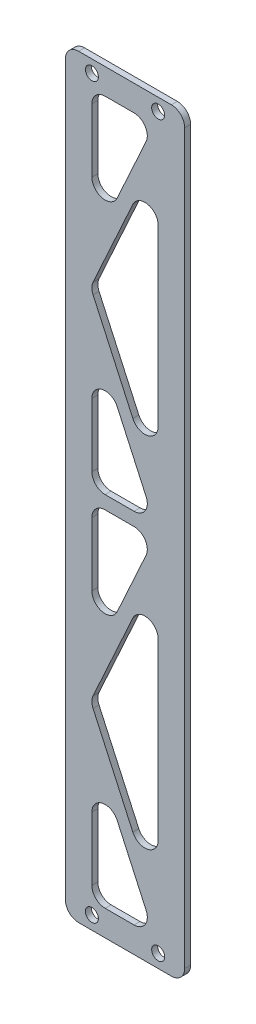
SolidWorks part; units mm, degrees
material "6061-T6 (SS)"
ref_plane "Front Plane" through (0, 0, 0) normal (0, 0, 1) x (1, 0, 0)
ref_plane "Top Plane" through (0, 0, 0) normal (0, 1, 0) x (1, 0, 0)
ref_plane "Right Plane" through (0, 0, 0) normal (1, 0, 0) x (0, 0, -1)
sketch "Sketch1" plane through (0, 0, 0) normal (0, 0, 1) x (1, 0, 0)
  line L0 (-5.08, -5.08) -> (30.48, -5.08)
  line L1 (35.56, 0) -> (35.56, 279.4)
  line L2 (30.48, 284.48) -> (-5.08, 284.48)
  line L3 (-10.16, 279.4) -> (-10.16, 0)
  line L6 (16.1606, 274.32) -> (0, 274.32)
  line L7 (0, 274.32) -> (0, 107.6181)
  line L10 (28.1496, 4.7625) -> (-49966.223, 4.7625) construction
  line L11 (20.7828, 11.9499) -> (9.7022, 36.253)
  line L12 (1052.7568, 4.7625) -> (24.0598, 4.7625) construction
  line L14 (5.08, 4.7625) -> (16.1606, 4.7625)
  line L15 (0.4578, 68.7744) -> (15.6978, 35.3485)
  line L17 (0, 34.1456) -> (0, 9.8425)
  line L18 (0, 70.8819) -> (-50000, 70.8819) construction
  line L19 (0.4578, 72.9893) -> (15.6978, 106.4153)
  line L20 (0, 107.6181) -> (0, 131.9213)
  line L21 (20.7828, 129.8138) -> (9.7022, 105.5107)
  line L22 (5.08, 137.0013) -> (16.1606, 137.0013)
  line L23 (12.7, -5.08) -> (12.7, 49994.92) construction
  line L24 (-10.16, 139.5413) -> (-50010.16, 139.5412) construction
  line L25 (30.48, -5.3975) -> (-5.08, -5.3975)
  line L26 (35.56, 279.0825) -> (35.56, -0.3175)
  line L27 (-5.08, 284.1625) -> (30.48, 284.1625)
  line L28 (-10.16, -0.3175) -> (-10.16, 279.0825)
  line L29 (0.4578, 210.3081) -> (15.6978, 243.734)
  line L30 (0.4578, 206.0932) -> (15.6978, 172.6672)
  line L31 (20.7828, 149.2687) -> (9.7022, 173.5718)
  line L32 (5.08, 142.0813) -> (16.1606, 142.0813)
  line L33 (0, 171.4644) -> (0, 147.1612)
  line L34 (0, 244.9369) -> (0, 269.24)
  line L35 (20.7828, 267.1326) -> (9.7022, 242.8295)
  line L36 (5.08, 274.32) -> (16.1606, 274.32)
  line L37 (25.4, 174.7746) -> (25.4, 241.6266)
  line L38 (25.4, 104.3079) -> (25.4, 37.4559)
  arc A24 (-5.08, 284.48) -> (-10.16, 279.4) centre (-5.08, 279.4) ccw
  arc A25 (35.56, 279.4) -> (30.48, 284.48) centre (30.48, 279.4) ccw
  arc A26 (30.48, -5.08) -> (35.56, 0) centre (30.48, 0) ccw
  arc A27 (-5.08, -5.08) -> (-10.16, 0) centre (-5.08, 0) cw
  arc A28 (0.4578, 72.9893) -> (0.4578, 68.7744) centre (5.08, 70.8819) ccw
  arc A29 (15.6978, 35.3485) -> (25.4, 37.4559) centre (20.32, 37.4559) ccw
  arc A30 (5.08, 4.7625) -> (0, 9.8425) centre (5.08, 9.8425) cw
  arc A31 (9.7022, 36.253) -> (0, 34.1456) centre (5.08, 34.1456) ccw
  arc A32 (20.7828, 11.9499) -> (16.1606, 4.7625) centre (16.1606, 9.8425) cw
  arc A33 (15.6978, 106.4153) -> (25.4, 104.3079) centre (20.32, 104.3079) cw
  arc A34 (9.7022, 105.5107) -> (0, 107.6181) centre (5.08, 107.6181) cw
  arc A35 (5.08, 137.0013) -> (0, 131.9213) centre (5.08, 131.9213) ccw
  arc A36 (20.7828, 129.8138) -> (16.1606, 137.0013) centre (16.1606, 131.9213) ccw
  arc A37 (15.6978, 172.6672) -> (25.4, 174.7746) centre (20.32, 174.7746) ccw
  arc A38 (35.56, -0.3175) -> (30.48, -5.3975) centre (30.48, -0.3175) cw
  arc A39 (30.48, 284.1625) -> (35.56, 279.0825) centre (30.48, 279.0825) cw
  arc A40 (-5.08, -5.3975) -> (-10.16, -0.3175) centre (-5.08, -0.3175) cw
  arc A41 (-5.08, 284.1625) -> (-10.16, 279.0825) centre (-5.08, 279.0825) ccw
  arc A42 (15.6978, 243.734) -> (25.4, 241.6266) centre (20.32, 241.6266) cw
  arc A43 (0.4578, 206.0932) -> (0.4578, 210.3081) centre (5.08, 208.2006) cw
  arc A44 (9.7022, 173.5718) -> (0, 171.4644) centre (5.08, 171.4644) ccw
  arc A45 (20.7828, 149.2687) -> (16.1606, 142.0813) centre (16.1606, 147.1612) cw
  arc A46 (5.08, 142.0813) -> (0, 147.1612) centre (5.08, 147.1612) cw
  arc A47 (9.7022, 242.8295) -> (0, 244.9369) centre (5.08, 244.9369) cw
  arc A48 (5.08, 274.32) -> (0, 269.24) centre (5.08, 269.24) ccw
  arc A49 (20.7828, 267.1326) -> (16.1606, 274.32) centre (16.1606, 269.24) ccw
  circle A50 centre (0, 279.4) radius 2.4892
  circle A51 centre (25.4, 279.4) radius 2.4892
  circle A52 centre (25.4, 0) radius 2.4892
  circle A53 centre (0, 0) radius 2.4892
  point P55 (0, 57.533)
  point P80 (12.7, -5.08)
  dimension "D8" = 5.08
  dimension "D9" = 5.08
  dimension "D1" = 5.08
  dimension "D2" = 5.08
  dimension "D3" = 10.16
  dimension "D4" = 22.86
  dimension "D5" = 5.08
  dimension "D6" = 10.16
  dimension "D7" = 10.16
  dimension "D10" = 134.7788
  dimension "D12" = 11.0806
  dimension "D13" = 2.54
extrude "Boss-Extrude1" add sketch "Sketch1" along normal blind 2.286
sketch "Sketch2" [suppressed] plane through (0, 0, 0) normal (0, 0, 1) x (1, 0, 0)
  line L0 (-10.16, 139.5413) -> (35.56, 139.5413) construction
  line L1 (-10.16, 279.0825) -> (-10.16, 0) construction
  line L2 (35.56, 0) -> (35.56, 279.0825) construction
  circle A0 centre (11.1513, 150.9931) radius 2.54
  circle A1 centre (11.1513, 265.8166) radius 2.54
  circle A2 centre (17.3447, 224.9694) radius 2.54
  circle A3 centre (17.3447, 191.4897) radius 2.54
  circle A4 centre (6.8102, 162.3333) radius 2.54
  circle A5 centre (6.8102, 254.7484) radius 2.54
  circle A6 centre (11.1513, 13.2659) radius 2.54
  circle A7 centre (6.8102, 24.3341) radius 2.54
  circle A8 centre (17.3447, 54.1131) radius 2.54
  circle A9 centre (17.3447, 87.5928) radius 2.54
  circle A10 centre (11.1513, 128.0894) radius 2.54
  circle A11 centre (6.8102, 116.7492) radius 2.54
  point P14 (11.0373, 149.9801)
  point P17 (5.1968, 161.6611)
  point P18 (0, 0)
  point P19 (6.8124, 161.0338)
  point P20 (12.5804, 149.6688)
  point P21 (6.8102, 162.3333)
  point P22 (0, 0)
  point P23 (11.1513, 150.9931)
  point P24 (17.8678, 188.0894)
  point P25 (15.1214, 219.869)
  point P26 (17.3447, 191.4897)
  point P27 (17.3447, 224.9694)
  point P28 (6.8102, 267.2323)
  point P31 (6.8102, 254.7484)
  point P32 (11.1513, 265.8166)
  dimension "D1" = 5.08
fillet "Fillet1" radius 5.08 1 edges at (0, 274.32, 1.143)
